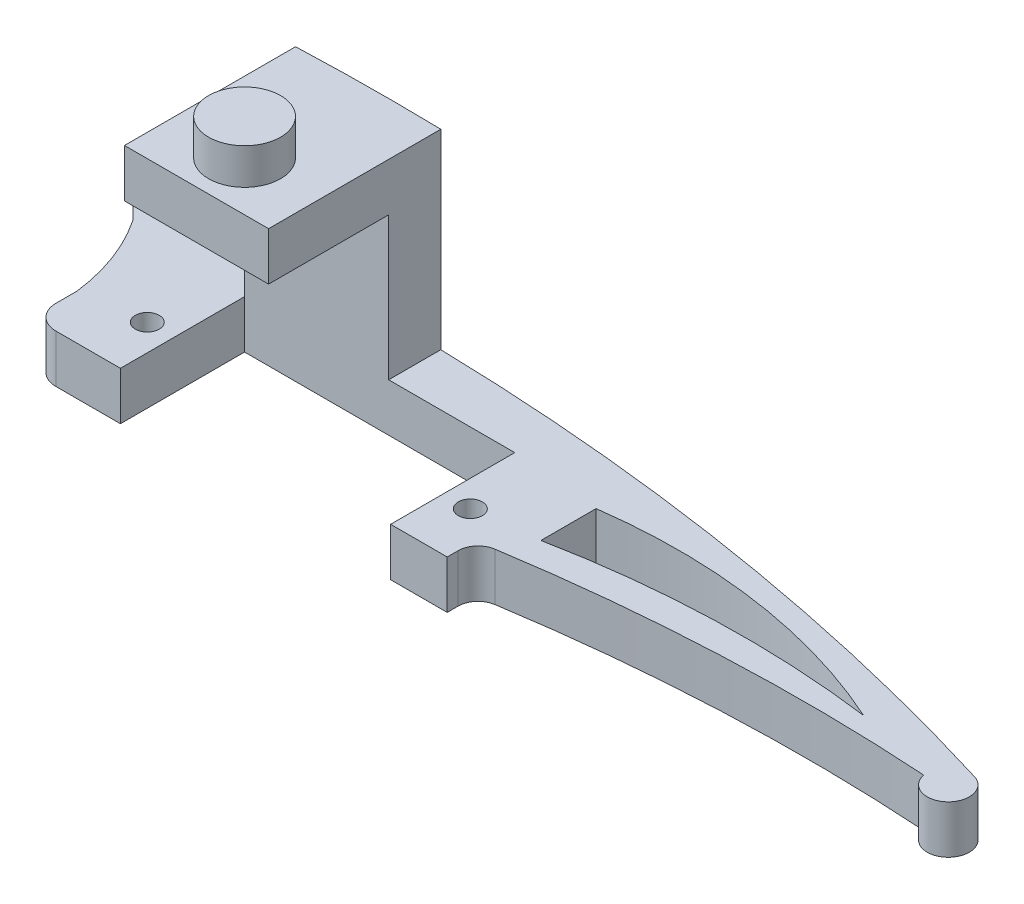
SolidWorks part; units mm, degrees
ref_plane "Front Plane" through (0, 0, 0) normal (0, 0, 1) x (1, 0, 0)
ref_plane "Top Plane" through (0, 0, 0) normal (0, 1, 0) x (1, 0, 0)
ref_plane "Right Plane" through (0, 0, 0) normal (1, 0, 0) x (0, 0, -1)
sketch "Sketch1" plane through (0, 0, 0) normal (0, 1, 0) x (1, 0, 0)
  line L0 (0, 0) -> (78.5, 0) construction
  line L1 (14, 0) -> (14, 5.9)
  line L2 (14, 5.9) -> (36.5, 5.9)
  line L3 (36.5, 5.9) -> (36.5, 0)
  line L4 (36.5, 0) -> (36.5, -4.4385)
  line L5 (36.5, -4.4385) -> (41.2135, -4.4385)
  line L6 (41.2135, -4.4385) -> (41.2135, -3.5362)
  line L7 (14, 0) -> (14, -4.4385)
  line L8 (14, -4.4385) -> (8.6263, -4.4385)
  line L9 (6.6263, -2.4385) -> (6.6263, -0.6969)
  line L10 (0, 0) -> (0, 19.9753) construction
  line L11 (0.3995, 10.2103) -> (3.8219, 6.7879)
  line L12 (43.9243, 5.25) -> (43.9243, 0.65)
  circle A0 centre (11.8, 0) radius 1
  circle A1 centre (38.7, 0) radius 1
  arc A2 (76.7808, -0.327) -> (79.0134, 1.673) centre (78.5, 0) ccw
  arc A3 (42.6218, -1.8878) -> (76.7808, -0.327) centre (66.695, -154.1701) cw
  arc A4 (79.0134, 1.673) -> (10.0717, 9.9549) centre (21.5542, -185.5486) ccw
  arc A5 (1.6203, 12.5146) -> (0.3995, 10.2103) centre (1.3641, 11.1748) ccw
  arc A6 (10.0717, 9.9549) -> (1.6203, 12.5146) centre (-6.2837, -28.8142) ccw
  arc A7 (3.8219, 6.7879) -> (6.6263, -0.6969) centre (-10.1705, -2.7226) cw
  arc A8 (8.6263, -4.4385) -> (6.6263, -2.4385) centre (8.6263, -2.4385) cw
  arc A9 (41.2135, -3.5362) -> (42.6218, -1.8878) centre (42.8824, -3.5362) cw
  arc A10 (43.9243, 0.65) -> (69.9814, 1.4684) centre (59.4329, -77.9048) cw
  arc A11 (69.9814, 1.4684) -> (43.9243, 5.25) centre (50.3928, -41.8431) ccw
  circle A14 centre (19.9, 0) radius 3 construction
  point P3 (14, 0)
  point P4 (36.5, 0)
  point P37 (36.5, 2.95)
  point P38 (43.9243, 2.95)
  point P42 (19.9, 0)
  dimension "D3" = 2
  dimension "D8" = 3.5
  dimension "D10" = 2
  dimension "D11" = 1.6689
  dimension "D14" = 6
  dimension "D1" = 78.5
  dimension "D2" = 22.5
  dimension "D4" = 2.2
  dimension "D5" = 2.2
  dimension "D6" = 14
  dimension "D7" = 5.9
  dimension "D9" = 2
  dimension "D12" = 4.6
  dimension "D13" = 5.9
extrude "Boss-Extrude1" add sketch "Sketch1" along normal mid plane 4
sketch "Sketch2" plane through (0, 2, 0) normal (0, 1, 0) x (1, 0, 0)
  line L3 (14, 5.9) -> (14, 10.1461)
  line L4 (26, 5.9) -> (26, 10.2414)
  line L10 (14, -4.4385) -> (14, 5.9)
  line L11 (14, 5.9) -> (36.5, 5.9)
  line L12 (36.5, 5.9) -> (36.5, -4.4385)
  line L13 (36.5, -4.4385) -> (41.2135, -4.4385)
  line L14 (41.2135, -4.4385) -> (41.2135, -3.5362)
  line L15 (0.3995, 10.2103) -> (3.8219, 6.7879)
  line L16 (6.6263, -0.6969) -> (6.6263, -2.4385)
  line L17 (8.6263, -4.4385) -> (14, -4.4385)
  line L19 (14, 5.9) -> (26, 5.9)
  arc A8 (42.6218, -1.8878) -> (41.2135, -3.5362) centre (42.8824, -3.5362) ccw
  arc A9 (76.7808, -0.327) -> (42.6218, -1.8878) centre (66.695, -154.1701) ccw
  arc A10 (76.7808, -0.327) -> (79.0134, 1.673) centre (78.5, 0) ccw
  arc A11 (79.0134, 1.673) -> (10.0717, 9.9549) centre (21.5542, -185.5486) ccw
  arc A12 (10.0717, 9.9549) -> (1.6203, 12.5146) centre (-6.2837, -28.8142) ccw
  arc A13 (1.6203, 12.5146) -> (0.3995, 10.2103) centre (1.3641, 11.1748) ccw
  arc A14 (6.6263, -0.6969) -> (3.8219, 6.7879) centre (-10.1705, -2.7226) ccw
  arc A15 (6.6263, -2.4385) -> (8.6263, -4.4385) centre (8.6263, -2.4385) ccw
  arc A19 (26, 10.2414) -> (14, 10.1461) centre (21.5542, -185.5486) ccw
  dimension "D1" = 0
extrude "Boss-Extrude2" add sketch "Sketch2" along normal blind 15.9
sketch "Sketch3" plane through (0, 0, -5.9) normal (0, 0, 1) x (1, 0, 0)
  line L0 (14, 13.9) -> (26, 13.9)
  line L7 (14, -2) -> (36.5, -2)
  line L8 (36.5, -2) -> (36.5, 2)
  line L9 (36.5, 2) -> (26, 2)
  line L10 (26, 2) -> (26, 17.9)
  line L11 (26, 17.9) -> (14, 17.9)
  line L12 (14, 17.9) -> (14, 2)
  line L13 (14, 2) -> (14, -2)
  line L17 (26, 13.9) -> (26, 17.9)
  line L18 (26, 17.9) -> (14, 17.9)
  line L19 (14, 17.9) -> (14, 13.9)
  dimension "D2" = 4
  dimension "D1" = 0
extrude "Boss-Extrude3" add sketch "Sketch3" along normal blind 10
sketch "Sketch5" plane through (0, 17.9, 0) normal (0, 1, 0) x (1, 0, 0)
  circle A5 centre (19.9, 0) radius 3 construction
  circle A6 centre (19.9, 0) radius 3
extrude "Boss-Extrude4" add sketch "Sketch5" along normal blind 3
